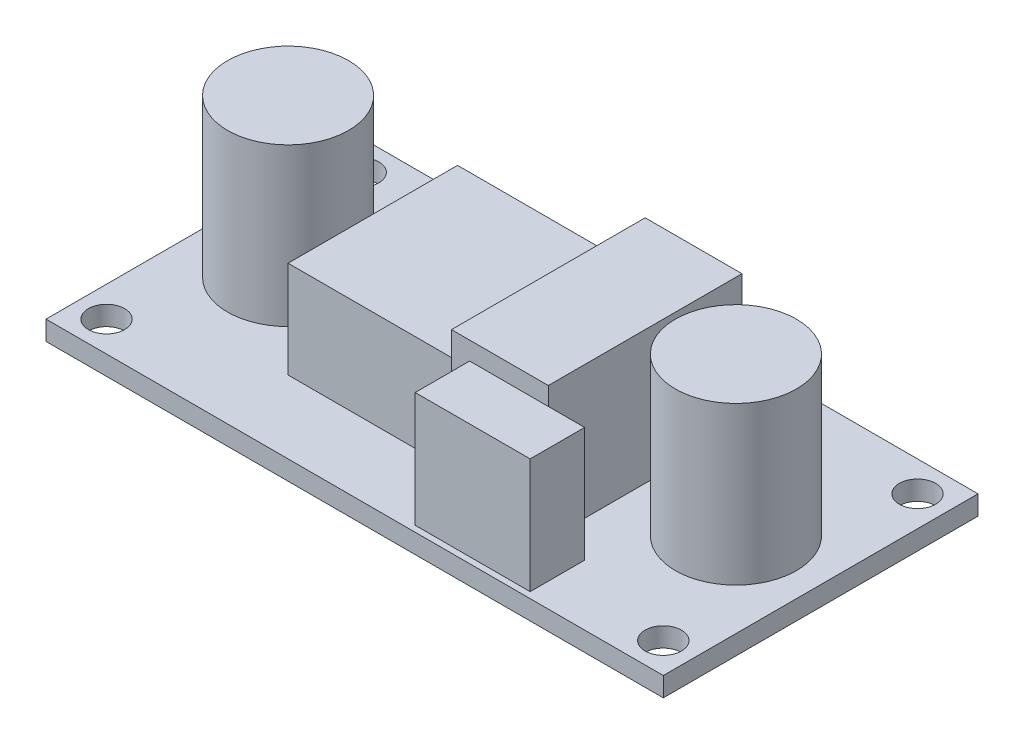
SolidWorks part; units mm, degrees
ref_plane "Front Plane" through (0, 0, 0) normal (0, 0, 1) x (1, 0, 0)
ref_plane "Top Plane" through (0, 0, 0) normal (0, 1, 0) x (1, 0, 0)
ref_plane "Right Plane" through (0, 0, 0) normal (1, 0, 0) x (0, 0, -1)
other "Configuration Table"
sketch "Sketch1" plane through (0, 0, 0) normal (0, 1, 0) x (1, 0, 0)
  line L1 (0, 0) -> (51, 0)
  line L2 (0, 0) -> (0, 26)
  line L3 (0, 26) -> (51, 26)
  line L4 (51, 0) -> (51, 26)
extrude "PCB" add sketch "Sketch1" along normal blind 1.6
sketch "Sketch2" plane through (0, 0, 0) normal (0, 1, 0) x (1, 0, 0)
  circle A0 centre (2.5, 2.5) radius 1.5
extrude "Mount_hole_1" cut sketch "Sketch2" against normal through all and the other way through all
sketch "Sketch3" plane through (0, 0, 0) normal (0, 1, 0) x (1, 0, 0)
  circle A0 centre (48.5, 2.5) radius 1.5
extrude "Mount_hole_2" cut sketch "Sketch3" against normal through all and the other way through all
sketch "Sketch4" plane through (0, 0, 0) normal (0, 1, 0) x (1, 0, 0)
  circle A0 centre (2.5, 23.5) radius 1.5
extrude "Mount_hole_3" cut sketch "Sketch4" against normal through all and the other way through all
sketch "Sketch5" plane through (0, 0, 0) normal (0, 1, 0) x (1, 0, 0)
  circle A0 centre (48.5, 23.5) radius 1.5
extrude "Mount_hole_4" cut sketch "Sketch5" against normal through all and the other way through all
sketch "Sketch6" plane through (0, 0, 0) normal (0, 1, 0) x (1, 0, 0)
  line L1 (14, 6) -> (28, 6)
  line L2 (14, 6) -> (14, 20)
  line L3 (14, 20) -> (28, 20)
  line L4 (28, 6) -> (28, 20)
extrude "Inductor" add sketch "Sketch6" along normal blind 8 from offset 1.6
sketch "Sketch7" plane through (0, 0, 0) normal (0, 1, 0) x (1, 0, 0)
  circle A0 centre (7, 13) radius 5
extrude "Cap_in" add sketch "Sketch7" along normal blind 13 from offset 1.6
sketch "Sketch8" plane through (0, 0, 0) normal (0, 1, 0) x (1, 0, 0)
  circle A0 centre (44, 13) radius 5
extrude "Cap_out" add sketch "Sketch8" along normal blind 13 from offset 1.6
sketch "Sketch9" plane through (0, 0, 0) normal (0, 1, 0) x (1, 0, 0)
  line L1 (28.5, 5) -> (36.5, 5)
  line L2 (28.5, 5) -> (28.5, 21)
  line L3 (28.5, 21) -> (36.5, 21)
  line L4 (36.5, 5) -> (36.5, 21)
extrude "Heatsink" add sketch "Sketch9" along normal blind 11 from offset 1.6
sketch "Sketch10" plane through (0, 0, 0) normal (0, 1, 0) x (1, 0, 0)
  line L1 (30, 0.5) -> (39.5, 0.5)
  line L2 (30, 0.5) -> (30, 5)
  line L3 (30, 5) -> (39.5, 5)
  line L4 (39.5, 0.5) -> (39.5, 5)
extrude "Trim_pot" add sketch "Sketch10" along normal blind 9.5 from offset 1.6
